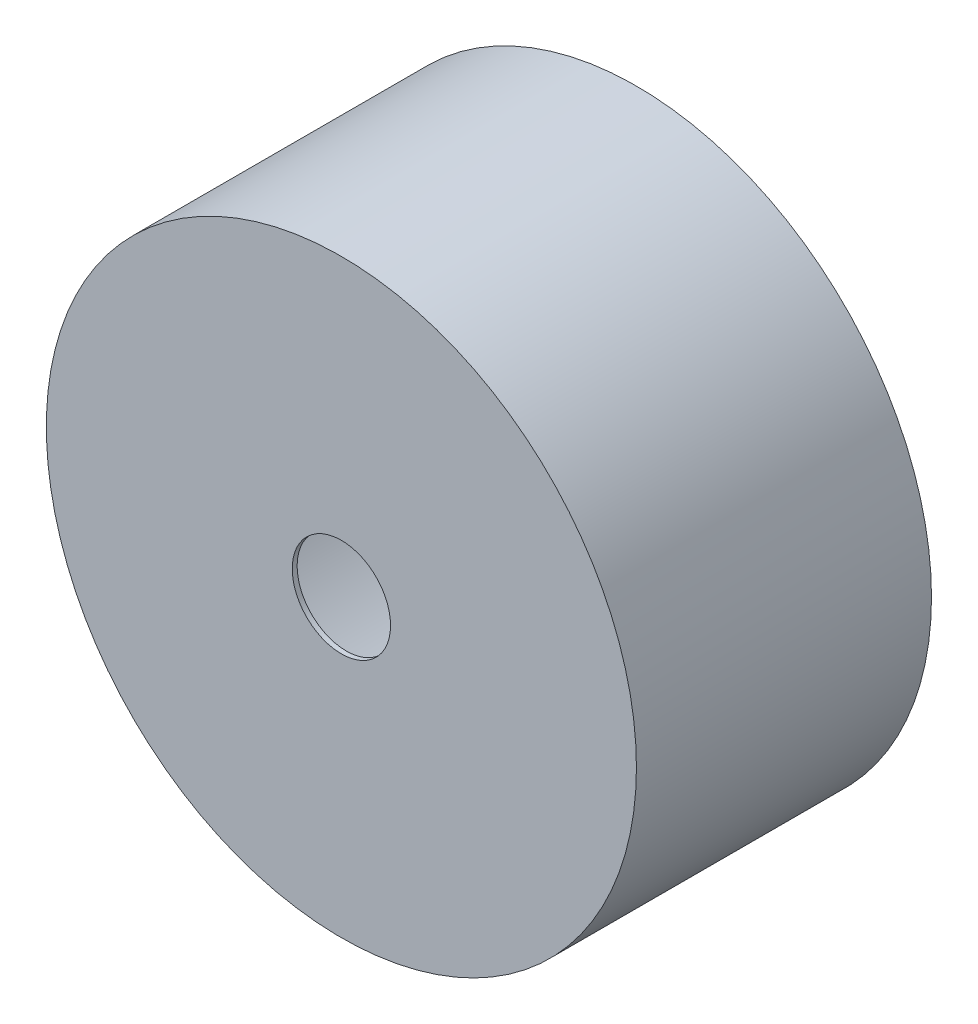
SolidWorks part; units mm, degrees
ref_plane "Front Plane" through (0, 0, 0) normal (0, 0, 1) x (1, 0, 0)
ref_plane "Top Plane" through (0, 0, 0) normal (0, 1, 0) x (1, 0, 0)
ref_plane "Right Plane" through (0, 0, 0) normal (1, 0, 0) x (0, 0, -1)
sketch "Sketch1" plane through (0, 0, 0) normal (0, 0, 1) x (1, 0, 0)
  line L5 (-4.92, -6.5) -> (4.92, 6.5) construction
  line L6 (-4.92, 6.5) -> (4.92, -6.5) construction
  circle A0 centre (0, 0) radius 3
  point P0 (0, 0)
extrude "Boss-Extrude2" add sketch "Sketch1" along normal blind 3
sketch "Sketch2" plane through (0, 0, 0) normal (0, 0, -1) x (-1, 0, 0)
  circle A0 centre (0, 0) radius 2.5
extrude "Cut-Extrude2" cut sketch "Sketch2" against normal blind 2.95
sketch "Sketch3" plane through (0, 0, 3) normal (0, 0, 1) x (1, 0, 0)
  circle A0 centre (0, 0) radius 0.5
extrude "Cut-Extrude3" cut sketch "Sketch3" against normal blind 3
